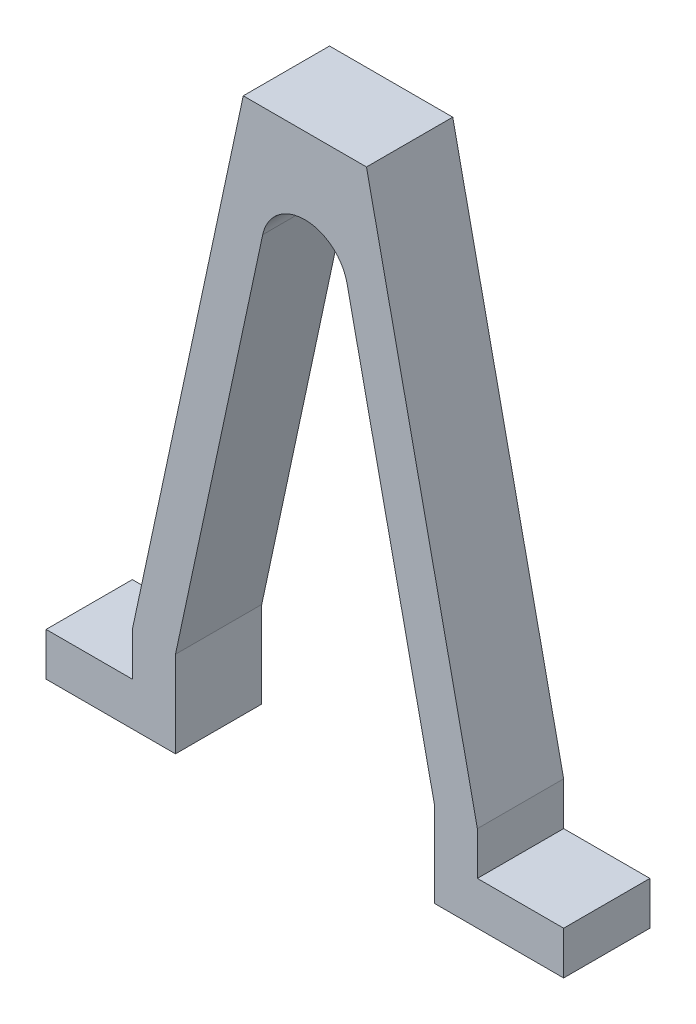
SolidWorks part; units mm, degrees
ref_plane "Front Plane" through (0, 0, 0) normal (0, 0, 1) x (1, 0, 0)
ref_plane "Top Plane" through (0, 0, 0) normal (0, 1, 0) x (1, 0, 0)
ref_plane "Right Plane" through (0, 0, 0) normal (1, 0, 0) x (0, 0, -1)
sketch "Sketch1" plane through (0, 0, 0) normal (0, 0, 1) x (1, 0, 0)
  line L0 (0, 0) -> (15, 0)
  line L3 (45, 0) -> (60, 0)
  line L4 (60, 0) -> (60, 5)
  line L5 (60, 5) -> (50, 5)
  line L6 (50, 5) -> (50, 10)
  line L7 (50, 10) -> (30, 103.3333)
  line L8 (30, 103.3333) -> (10, 10)
  line L9 (10, 10) -> (10, 5)
  line L10 (10, 5) -> (0, 5)
  line L11 (0, 5) -> (0, 0)
  line L12 (15, 0) -> (15, 10)
  line L13 (15, 10) -> (30, 80)
  line L14 (30, 80) -> (45, 10)
  line L15 (45, 10) -> (45, 0)
  point P4 (30, 63.3333)
  dimension "D1" = 5
  dimension "D2" = 30
  dimension "D3" = 15
  dimension "D4" = 15
  dimension "D5" = 10
  dimension "D6" = 10
  dimension "D7" = 5
  dimension "D8" = 80
extrude "Boss-Extrude1" add sketch "Sketch1" along normal blind 10
fillet "Fillet1" radius 5 1 edges at (30, 80, 5)
sketch "Sketch2" plane through (0, 0, 10) normal (0, 0, 1) x (1, 0, 0)
  line L0 (17.1801, 70) -> (46.9507, 70)
  line L1 (46.9507, 70) -> (40.8298, 121.0129)
  line L2 (40.8298, 121.0129) -> (-8.692, 121.0129)
  line L3 (-8.692, 121.0129) -> (17.1801, 70)
  line L4 (45, 0) -> (60, 0) construction
  dimension "D1" = 70
extrude "Cut-Extrude1" cut sketch "Sketch2" against normal blind 10
